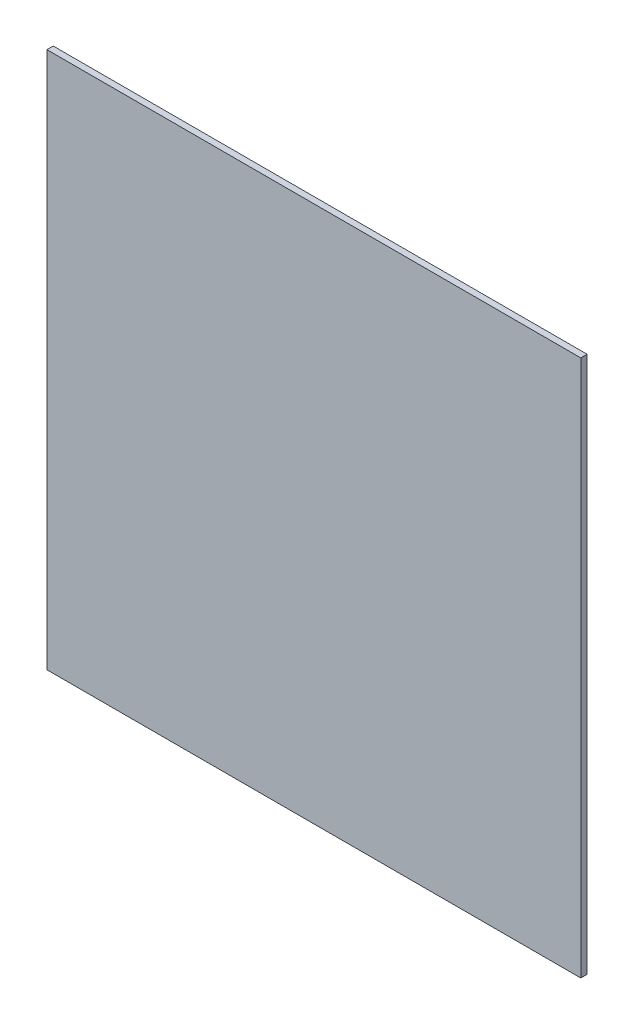
SolidWorks part; units mm, degrees
ref_plane "Front Plane" through (0, 0, 0) normal (0, 0, 1) x (1, 0, 0)
ref_plane "Top Plane" through (0, 0, 0) normal (0, 1, 0) x (1, 0, 0)
ref_plane "Right Plane" through (0, 0, 0) normal (1, 0, 0) x (0, 0, -1)
sketch "Model" plane through (0, 0, 0) normal (0, 0, 1) x (1, 0, 0)
  line L1 (84.5, -85) -> (-84.5, -85)
  line L2 (84.5, -85) -> (84.5, 85)
  line L3 (84.5, 85) -> (-84.5, 85)
  line L4 (-84.5, -85) -> (-84.5, 85)
  line L5 (84.5, -85) -> (-84.5, 85) construction
  line L6 (84.5, 85) -> (-84.5, -85) construction
  point P0 (0, 0)
  dimension "D1" = 169
  dimension "D2" = 170
extrude "Boss-Extrude1" add sketch "Model" along normal blind 2
